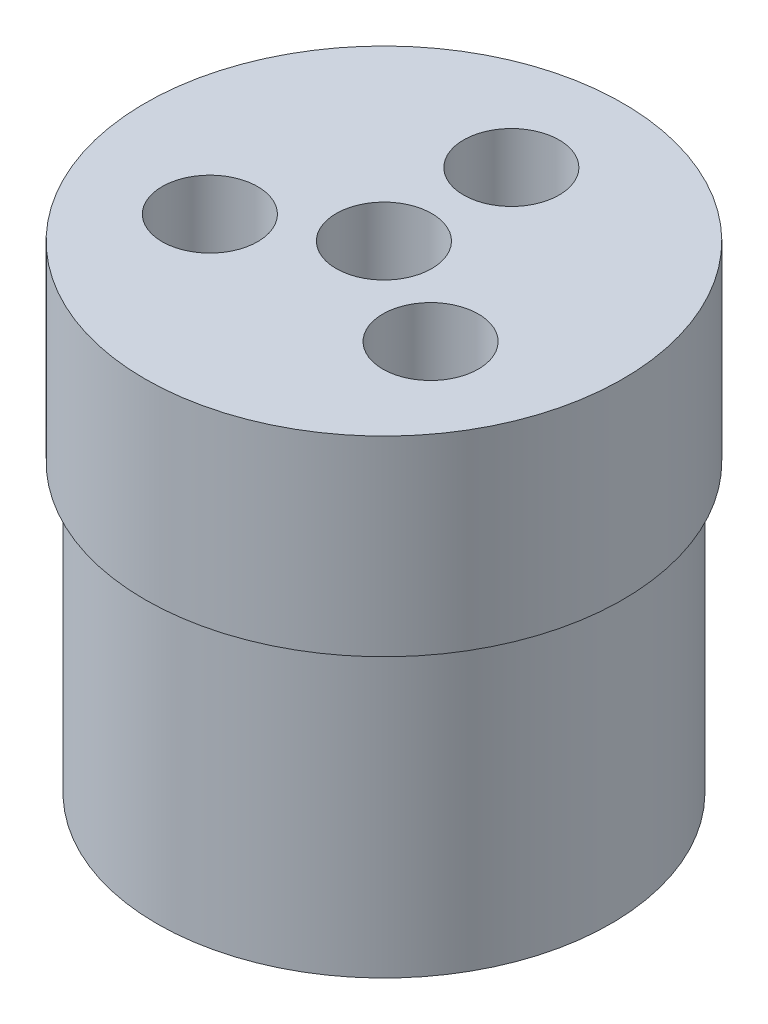
SolidWorks part; units mm, degrees
ref_plane "정면" through (0, 0, 0) normal (0, 0, 1) x (1, 0, 0)
ref_plane "윗면" through (0, 0, 0) normal (0, 1, 0) x (1, 0, 0)
ref_plane "우측면" through (0, 0, 0) normal (1, 0, 0) x (0, 0, -1)
sketch "스케치1" plane through (0, 0, 0) normal (0, 1, 0) x (1, 0, 0)
  circle A0 centre (0, 0) radius 14.25
  dimension "D1" = 28.5
extrude "보스-돌출1" add sketch "스케치1" along normal mid plane 30
hole_wizard "Ø6.0 (6) 지름 구멍1" positions "스케치2" profile "스케치3" hole size "Ø6.0" standard "KS" end condition through all
sketch "스케치2" plane through (0, 15, 0) normal (0, 1, 0) x (1, 0, 0)
  point P0 (0, 0)
sketch "스케치3" plane through (0, 15, 0) normal (1, 0, 0) x (0, 0, 1)
  line L0 (0, 0) -> (0, 30)
  line L1 (0, 30) -> (3, 30)
  line L2 (3, 30) -> (3, 0)
  line L5 (3, 0) -> (0, 0)
  line L11 (0, -6.35) -> (0, 107.95) construction
  dimension "관통 구멍 지름" = 6
  dimension "관통 구멍 깊이" = 30
hole_wizard "Ø6.0 (6) 지름 구멍2" positions "스케치4" profile "스케치5" hole size "Ø6.0" standard "KS" end condition through all
sketch "스케치4" plane through (0, 15, 0) normal (0, 1, 0) x (1, 0, 0)
  point P0 (0, 8)
  dimension "D1" = 8
sketch "스케치5" plane through (0, 15, -8) normal (1, 0, 0) x (0, 0, 1)
  line L0 (0, 0) -> (0, 30)
  line L1 (0, 30) -> (3, 30)
  line L2 (3, 30) -> (3, 0)
  line L5 (3, 0) -> (0, 0)
  line L11 (0, -6.35) -> (0, 107.95) construction
  dimension "관통 구멍 지름" = 6
  dimension "관통 구멍 깊이" = 30
pattern_circular "원형 패턴1" count 3 over 360 about axis through (0, 0, 0) along (0, 1, 0) of "Ø6.0 (6) 지름 구멍2"
sketch "스케치6" plane through (0, 15, 0) normal (0, 1, 0) x (1, 0, 0)
  circle A0 centre (0, 0) radius 15
  circle A7 centre (0, 0) radius 14.25 construction
  circle A12 centre (0, 0) radius 14.25
  circle M7 centre (0, 0) radius 14.25
  dimension "D1" = 30
extrude "보스-돌출2" add sketch "스케치6" against normal blind 12 contours A0 M7
